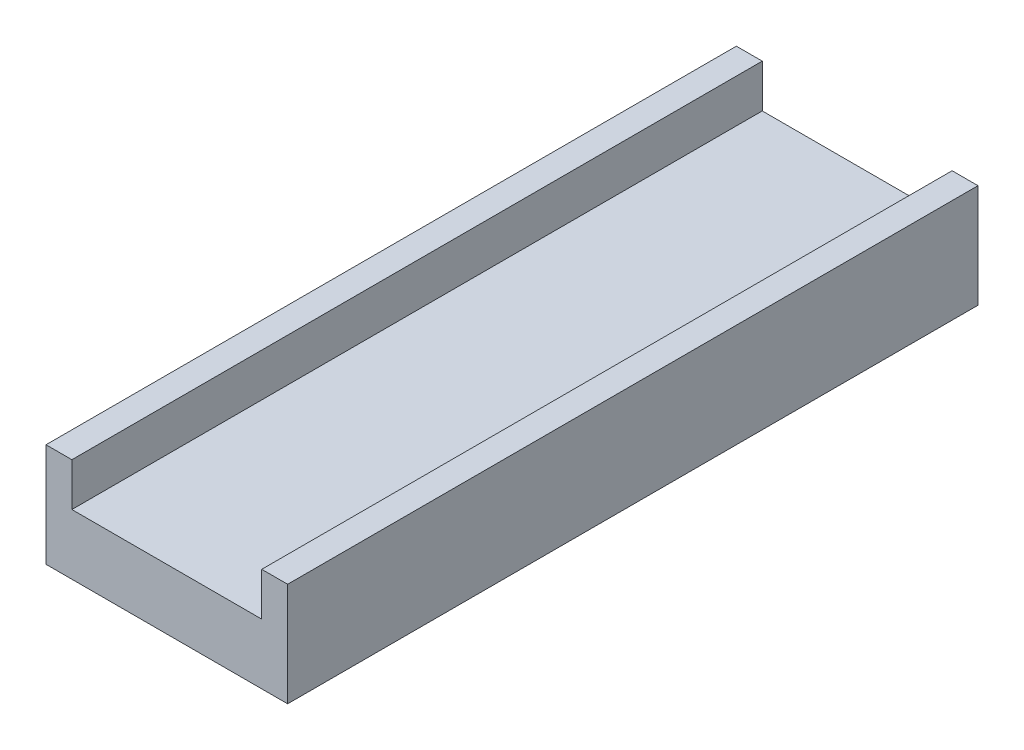
SolidWorks part; units mm, degrees
ref_plane "Front Plane" through (0, 0, 0) normal (0, 0, 1) x (1, 0, 0)
ref_plane "Top Plane" through (0, 0, 0) normal (0, 1, 0) x (1, 0, 0)
ref_plane "Right Plane" through (0, 0, 0) normal (1, 0, 0) x (0, 0, -1)
sketch "Sketch1" plane through (0, 0, 0) normal (0, 1, 0) x (1, 0, 0)
  line L1 (-14, 40) -> (14, 40)
  line L2 (-14, 40) -> (-14, -40)
  line L3 (-14, -40) -> (14, -40)
  line L4 (14, 40) -> (14, -40)
  line L5 (-14, 40) -> (14, -40) construction
  line L6 (-14, -40) -> (14, 40) construction
  point P0 (0, 0)
  dimension "D1" = 80
  dimension "D2" = 28
extrude "Boss-Extrude1" add sketch "Sketch1" along normal blind 2
sketch "Sketch2" plane through (0, 2, 0) normal (0, 1, 0) x (1, 0, 0)
  line L0 (-14, -40) -> (14, -40) construction
  line L1 (14, 40) -> (-14, 40)
  line L2 (14, 40) -> (14, -40)
  line L3 (14, -40) -> (-14, -40)
  line L4 (-14, 40) -> (-14, -40)
  dimension "D1" = 28
extrude "Boss-Extrude2" add sketch "Sketch2" along normal blind 10
sketch "Sketch3" plane through (0, 12, 0) normal (0, 1, 0) x (1, 0, 0)
  line L0 (14, 40) -> (-14, 40) construction
  line L1 (-11, 40) -> (11, 40)
  line L2 (-11, 40) -> (-11, -40)
  line L3 (-11, -40) -> (11, -40)
  line L4 (11, 40) -> (11, -40)
  line L5 (-14, -40) -> (14, -40) construction
  point P8 (0, 40)
  point P9 (0, 40)
  dimension "D1" = 22
extrude "Cut-Extrude1" cut sketch "Sketch3" against normal blind 5 contours L2 L3 L4 L1
